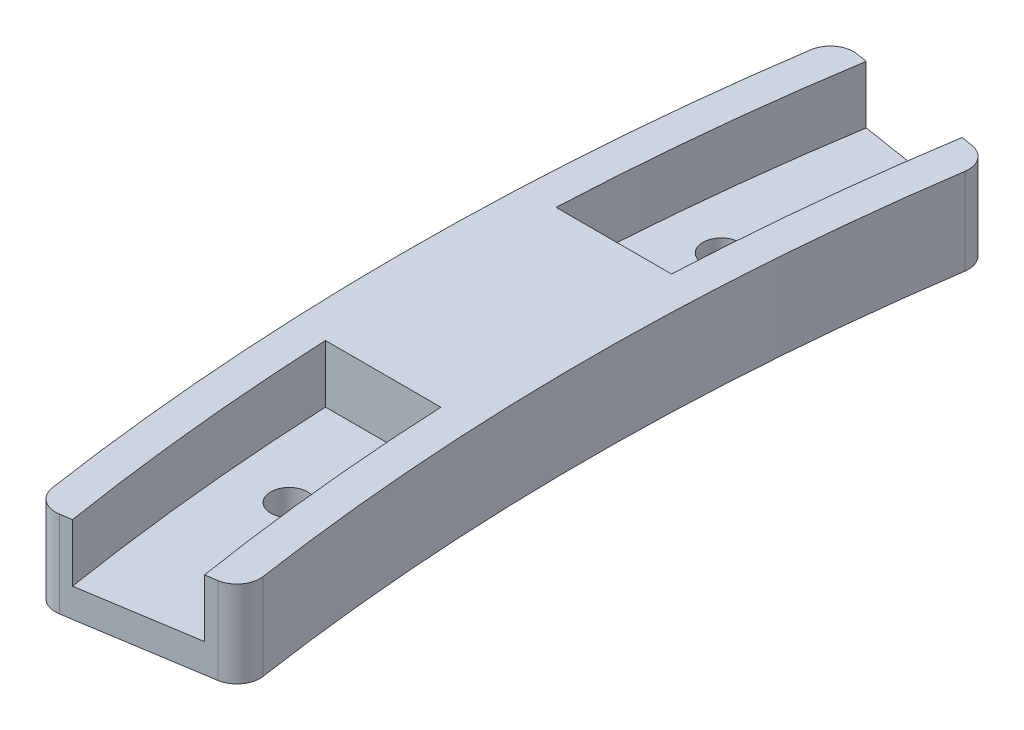
SolidWorks part; units mm, degrees
ref_plane "Front Plane" through (0, 0, 0) normal (0, 0, 1) x (1, 0, 0)
ref_plane "Top Plane" through (0, 0, 0) normal (0, 1, 0) x (1, 0, 0)
ref_plane "Right Plane" through (0, 0, 0) normal (1, 0, 0) x (0, 0, -1)
sketch "Sketch1" plane through (0, 0, 0) normal (0, 1, 0) x (1, 0, 0)
  line L0 (0, 0) -> (-217.2914, -34.4156) construction
  line L1 (0, 0) -> (-217.2914, 34.4156) construction
  line L2 (0, 0) -> (-215, 0) construction
  line L3 (-217.2914, 34.4156) -> (-207.4146, 32.8512)
  line L4 (-207.4146, -32.8512) -> (-217.2914, -34.4156)
  line L5 (0, 0) -> (-220.2545, -34.8849) construction
  line L6 (0, 0) -> (-220.2545, 34.8849) construction
  line L7 (-220.2545, 34.8849) -> (-204.4515, 32.3819)
  line L8 (-220.2545, -34.8849) -> (-204.4515, -32.3819)
  arc A0 (-217.2914, 34.4156) -> (-217.2914, -34.4156) centre (0, 0) ccw
  arc A1 (-207.4146, 32.8512) -> (-207.4146, -32.8512) centre (0, 0) ccw
  arc A2 (-212.353, -33.6334) -> (-212.353, 33.6334) centre (0, 0) cw construction
  arc A4 (-204.4515, 32.3819) -> (-204.4515, -32.3819) centre (0, 0) ccw
  arc A5 (-220.2545, 34.8849) -> (-220.2545, -34.8849) centre (0, 0) ccw
  dimension "D1" = 220
  dimension "D2" = 210
  dimension "D3" = 5
  dimension "D5" = 3
  dimension "D6" = 3
  dimension "D4" = 18
extrude "Boss-Extrude1" add sketch "Sketch1" along normal blind 10 contours A1 L3 A0 L4 | L7 A5 L8 A0 | A4 L7 A1 L8
ref_plane "Plane1" through (-215, 0, 0) normal (1, 0, 0) x (0, 0, -1)
sketch "Sketch15" plane through (0, 10, 0) normal (0, 1, 0) x (1, 0, 0)
  line L0 (-207.4146, -32.8512) -> (-217.2914, -34.4156) construction
  line L1 (-205, 10) -> (-225, 10)
  line L2 (-205, 10) -> (-205, -10)
  line L3 (-205, -10) -> (-225, -10)
  line L4 (-225, 10) -> (-225, -10)
  line L5 (-205, 10) -> (-225, -10) construction
  line L6 (-205, -10) -> (-225, 10) construction
  line L7 (-217.2914, 34.4156) -> (-207.4146, 32.8512) construction
  line L8 (-207.4146, -32.8512) -> (-217.2914, -34.4156)
  line L9 (-217.2914, 34.4156) -> (-207.4146, 32.8512)
  arc A2 (-207.4146, 32.8512) -> (-207.4146, -32.8512) centre (0, 0) ccw construction
  arc A3 (-217.2914, 34.4156) -> (-217.2914, -34.4156) centre (0, 0) ccw construction
  arc A4 (-207.4146, 32.8512) -> (-207.4146, -32.8512) centre (0, 0) ccw
  arc A5 (-217.2914, 34.4156) -> (-217.2914, -34.4156) centre (0, 0) ccw
  point P0 (-215, 0)
  line M5 (-220.2545, -34.8849) -> (-204.4515, -32.3819)
  line M7 (-204.4515, 32.3819) -> (-220.2545, 34.8849)
  dimension "D1" = 20
  dimension "D2" = 20
extrude "Cut-Extrude1" cut sketch "Sketch15" against normal blind 5 contours A5 L1 A4 M7 | L3 A5 A4 M5
ref_plane "Plane2" through (-215, 0, 0) normal (-1, 0, 0) x (0, 0, 1)
sketch "Sketch12" plane through (0, 0, 0) normal (0, 1, 0) x (1, 0, 0)
  line L0 (0, 0) -> (-214.1819, -18.7385) construction
  line L1 (0, 0) -> (-213.1606, -28.0631) construction
  line L2 (0, 0) -> (-215, 0) construction
  line L3 (0, 0) -> (-215, 0) construction
  line L4 (0, 0) -> (-214.1819, 18.7385) construction
  line L5 (0, 0) -> (-213.1606, 28.0631) construction
  arc A0 (-212.353, 33.6334) -> (-212.353, -33.6334) centre (0, 0) ccw construction
  dimension "D1" = 10
  dimension "D2" = 15
hole_wizard "Ø3.2 (3.2) Diameter Hole1" positions "Sketch18" profile "Sketch17" hole size "Ø3.2" standard "ISO" end condition through all
sketch "Sketch18" plane through (0, 0, 0) normal (0, -1, 0) x (-1, 0, 0)
  point P3 (214.1819, -18.7385)
  point P6 (214.1819, 18.7385)
  point P13 (0, 0)
  point P14 (0, 0)
sketch "Sketch17" plane through (-214.1819, 0, 18.7385) normal (1, 0, 0) x (0, 0, -1)
  line L0 (0, 0) -> (0, 10)
  line L1 (0, 10) -> (1.6, 10)
  line L2 (1.6, 10) -> (1.6, 0)
  line L5 (1.6, 0) -> (0, 0)
  line L11 (0, -6.35) -> (0, 107.95) construction
  dimension "Thru Hole Dia." = 3.2
  dimension "Thru Hole Depth" = 10
fillet "Fillet1" radius 2 4 edges at (-220.2545, 5, -34.8849) (-204.4515, 5, -32.3819) (-220.2545, 5, 34.8849) (-204.4515, 5, 32.3819)
sketch "Sketch19" plane through (0, 0, 0) normal (0, -1, 0) x (1, 0, 0)
  line L2 (-218.2702, -34.5706) -> (-206.4174, -32.6933)
  line L3 (-206.4174, 32.6933) -> (-218.2702, 34.5706)
  line L4 (-218.2702, -34.5706) -> (-206.4174, -32.6933)
  line L5 (-206.4174, 32.6933) -> (-218.2702, 34.5706)
  arc A6 (-220.5612, 32.8902) -> (-220.5612, -32.8902) centre (0, 0) ccw
  arc A7 (-220.5612, -32.8902) -> (-218.2702, -34.5706) centre (-218.5831, -32.5952) ccw
  arc A8 (-206.4174, -32.6933) -> (-204.752, -30.424) centre (-206.7303, -30.7179) ccw
  arc A9 (-204.752, 30.424) -> (-204.752, -30.424) centre (0, 0) ccw
  arc A10 (-204.752, 30.424) -> (-206.4174, 32.6933) centre (-206.7303, 30.7179) ccw
  arc A11 (-218.2702, 34.5706) -> (-220.5612, 32.8902) centre (-218.5831, 32.5952) ccw
  arc A12 (-220.5612, 32.8902) -> (-220.5612, -32.8902) centre (0, 0) ccw
  arc A13 (-220.5612, -32.8902) -> (-218.2702, -34.5706) centre (-218.5831, -32.5952) ccw
  arc A14 (-206.4174, -32.6933) -> (-204.752, -30.424) centre (-206.7303, -30.7179) ccw
  arc A15 (-204.752, 30.424) -> (-204.752, -30.424) centre (0, 0) ccw
  arc A16 (-204.752, 30.424) -> (-206.4174, 32.6933) centre (-206.7303, 30.7179) ccw
  arc A17 (-218.2702, 34.5706) -> (-220.5612, 32.8902) centre (-218.5831, 32.5952) ccw
  dimension "D1" = 0
extrude "Cut-Extrude2" cut sketch "Sketch19" against normal blind 2.5
